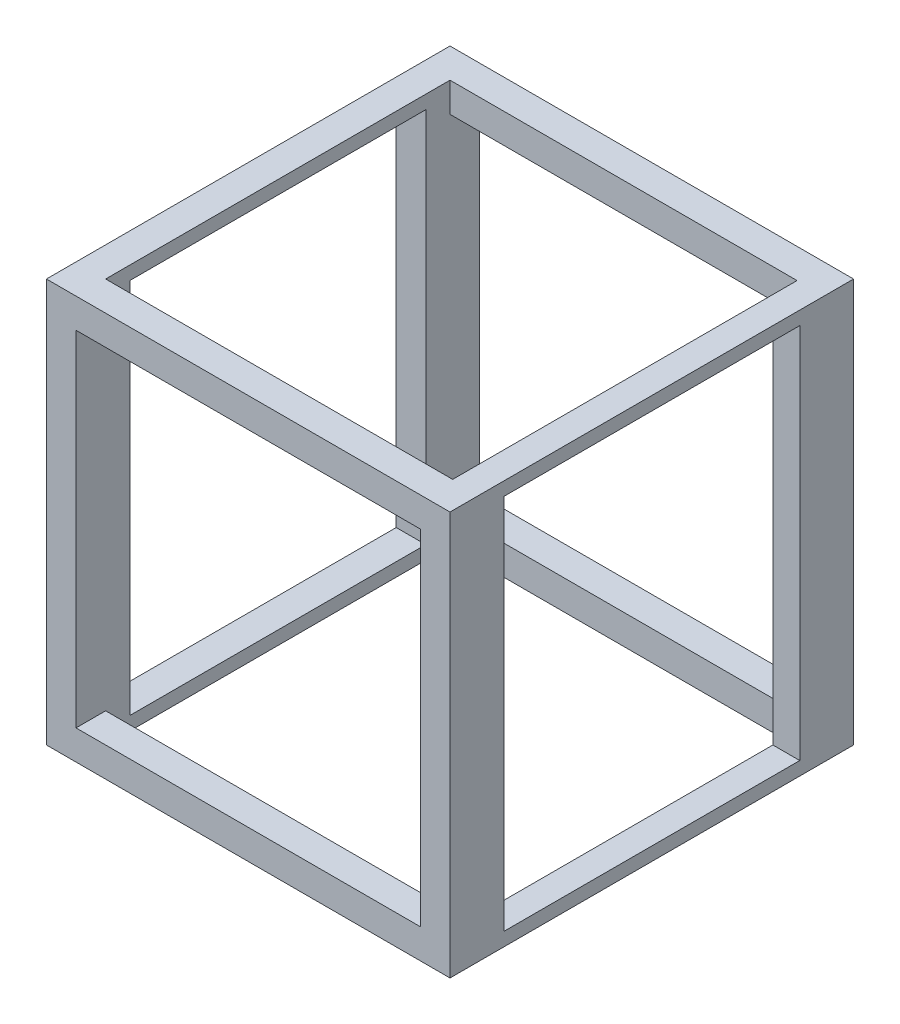
SolidWorks part; units mm, degrees
ref_plane "前视基准面" through (0, 0, 0) normal (0, 0, 1) x (1, 0, 0)
ref_plane "上视基准面" through (0, 0, 0) normal (0, 1, 0) x (1, 0, 0)
ref_plane "右视基准面" through (0, 0, 0) normal (1, 0, 0) x (0, 0, -1)
sketch "草图3" plane through (0, 0, 0) normal (0, 1, 0) x (1, 0, 0)
  line L1 (0, 0) -> (1500, 0)
  line L2 (0, 0) -> (0, 1500)
  line L3 (0, 1500) -> (1500, 1500)
  line L4 (1500, 0) -> (1500, 1500)
  dimension "D1" = 1500
  dimension "D2" = 1500
extrude "凸台-拉伸1" add sketch "草图3" along normal blind 1500
ref_plane "基准面1" through (0, 0, -1000) normal (0, 0, -1) x (-1, 0, 0)
ref_plane "基准面2" through (1000, 0, 0) normal (1, 0, 0) x (0, 0, -1)
sketch "草图4" plane through (1000, 0, 0) normal (1, 0, 0) x (0, 0, -1)
  line L0 (0, 1500) -> (0, 0) construction
  line L1 (1300, 50) -> (200, 50)
  line L2 (1300, 50) -> (1300, 1450)
  line L3 (1300, 1450) -> (200, 1450)
  line L4 (200, 50) -> (200, 1450)
  line L5 (1500, 1500) -> (1500, 0) construction
  line L6 (1500, 0) -> (0, 0) construction
  line L7 (1500, 1500) -> (0, 1500) construction
  dimension "D1" = 200
  dimension "D2" = 200
  dimension "D3" = 50
  dimension "D4" = 50
extrude "切除-拉伸1" cut sketch "草图4" against normal through all both and the other way through all from offset 0
sketch "草图5" plane through (0, 0, -1000) normal (0, 0, -1) x (-1, 0, 0)
  line L0 (-1500, 1500) -> (-1500, 0) construction
  line L1 (-1390, 1390) -> (-110, 1390)
  line L2 (-1390, 1390) -> (-1390, 110)
  line L3 (-1390, 110) -> (-110, 110)
  line L4 (-110, 1390) -> (-110, 110)
  line L5 (0, 1500) -> (0, 0) construction
  line L6 (0, 1500) -> (-1500, 1500) construction
  line L7 (0, 0) -> (-1500, 0) construction
  dimension "D1" = 110
  dimension "D2" = 110
  dimension "D3" = 110
  dimension "D4" = 110
extrude "切除-拉伸2" cut sketch "草图5" against normal through all both and the other way through all from offset 0
ref_plane "基准面3" through (0, 500, 0) normal (0, -1, 0) x (-1, 0, 0)
sketch "草图6" plane through (0, 500, 0) normal (0, -1, 0) x (-1, 0, 0)
  line L0 (-1500, 0) -> (-1500, 1500) construction
  line L1 (-1400, 110) -> (-110, 110)
  line L2 (-1400, 110) -> (-1400, 1390)
  line L3 (-1400, 1390) -> (-110, 1390)
  line L4 (-110, 110) -> (-110, 1390)
  line L5 (0, 0) -> (-1500, 0) construction
  line L6 (0, 1500) -> (0, 0) construction
  line L7 (-1500, 1500) -> (0, 1500) construction
  dimension "D1" = 100
  dimension "D2" = 110
  dimension "D3" = 110
  dimension "D4" = 110
extrude "切除-拉伸3" cut sketch "草图6" against normal through all both and the other way through all from offset 0
